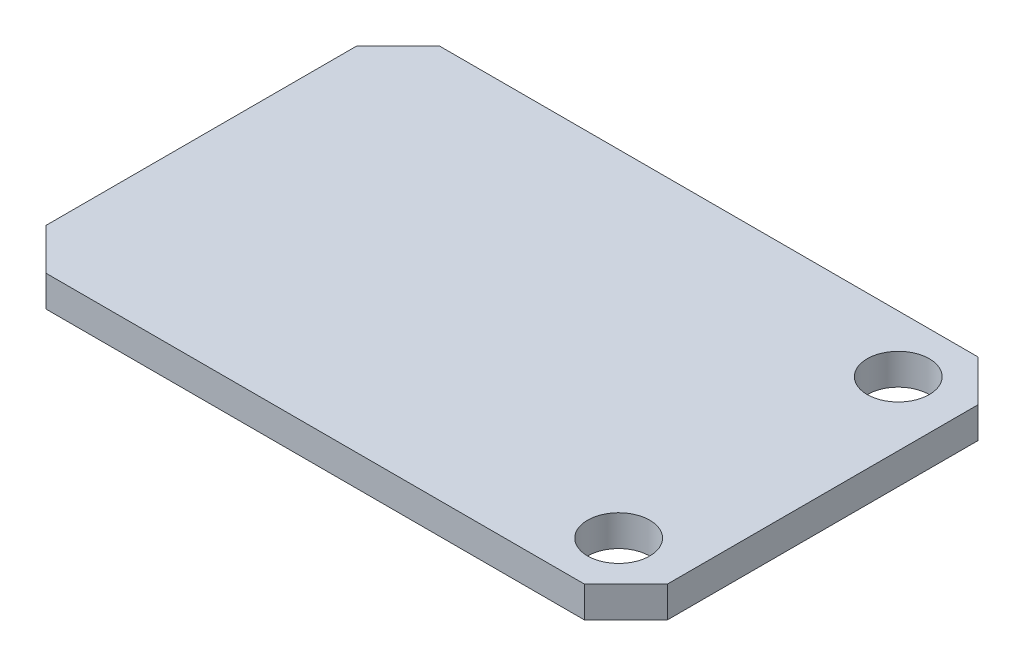
SolidWorks part; units mm, degrees
ref_plane "Спереди" through (0, 0, 0) normal (0, 0, 1) x (1, 0, 0)
ref_plane "Сверху" through (0, 0, 0) normal (0, 1, 0) x (1, 0, 0)
ref_plane "Справа" through (0, 0, 0) normal (1, 0, 0) x (0, 0, -1)
sketch "Эскиз1" plane through (0, 0, 0) normal (0, 1, 0) x (1, 0, 0)
  line L0 (11.9, 6.75) -> (11.9, -6.75) construction
  line L1 (-15, 9.5) -> (15, 9.5)
  line L2 (-15, 9.5) -> (-15, -9.5)
  line L3 (-15, -9.5) -> (15, -9.5)
  line L4 (15, 9.5) -> (15, -9.5)
  circle A0 centre (11.9, 6.75) radius 1.5
  circle A1 centre (11.9, -6.75) radius 1.5
  point P8 (11.9, 0)
  point P9 (11.9, -8.25)
  point P10 (15, 0)
  point P12 (0, 9.5)
  point P13 (11.9, 5.25)
  point P14 (11.9, -5.25)
  point P15 (13.4, 6.75)
  dimension "D3" = 3
  dimension "D1" = 30
  dimension "D2" = 19
  dimension "D4" = 10.5
  dimension "D5" = 1.6
extrude "Бобышка-Вытянуть1" add sketch "Эскиз1" along normal blind 1.5
chamfer "Фаска1" distance 2 angle 45 4 edges at (-15, 0.75, -9.5) (15, 0.75, -9.5) (15, 0.75, 9.5) (-15, 0.75, 9.5)
